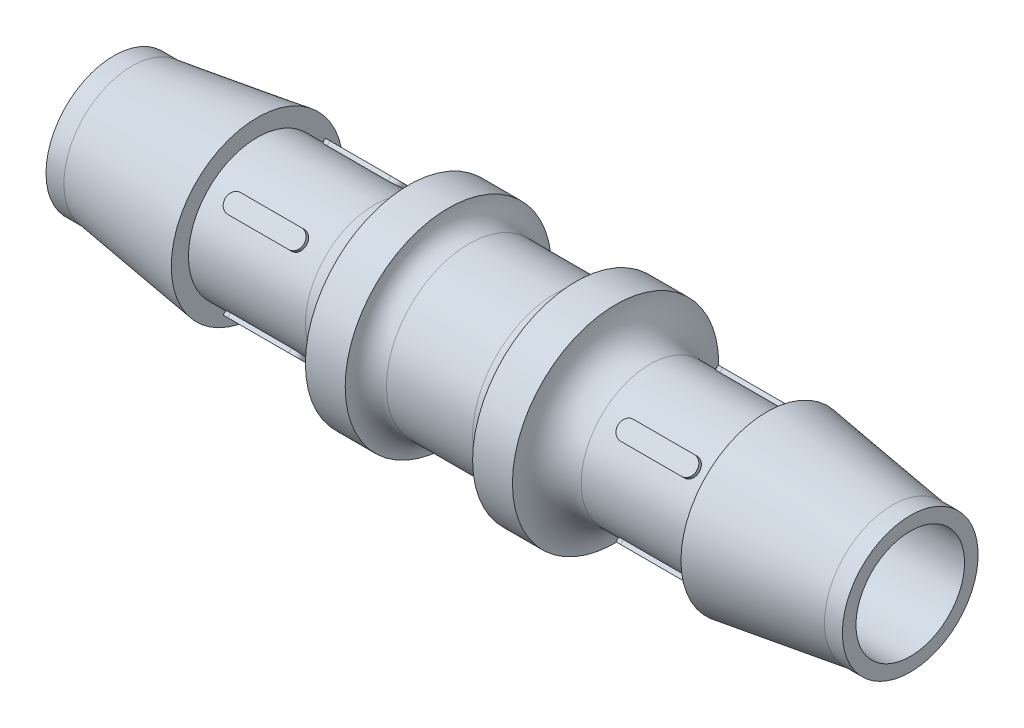
SolidWorks part; units mm, degrees
material "PVC 0.007 Plasticized"
ref_plane "Front Plane" through (0, 0, 0) normal (0, 0, 1) x (1, 0, 0)
ref_plane "Top Plane" through (0, 0, 0) normal (0, 1, 0) x (1, 0, 0)
ref_plane "Right Plane" through (0, 0, 0) normal (1, 0, 0) x (0, 0, -1)
sketch "Sketch1" plane through (0, 0, 0) normal (0, 0, 1) x (1, 0, 0)
  line L0 (0, 0) -> (33.528, 0) construction
  line L1 (33.528, 4.572) -> (33.528, 5.715)
  line L3 (21.4579, 7.239) -> (21.4579, 5.7912)
  line L4 (21.4579, 5.7912) -> (8.7173, 5.7912)
  line L5 (33.528, 5.715) -> (32.0192, 5.715)
  line L6 (8.7173, 5.7912) -> (8.7173, 8.6868)
  line L7 (8.7173, 8.6868) -> (5.3645, 8.6868)
  line L8 (5.3645, 8.6868) -> (5.3645, 6.9494)
  line L9 (5.3645, 6.9494) -> (0, 6.9494)
  line L10 (33.528, 4.572) -> (0, 4.572)
  line L11 (0, 4.572) -> (0, 6.9494)
  line L12 (15.4432, 6.5151) -> (21.4579, 6.5151) construction
  line L13 (0, 0) -> (0, -2.6412) construction
  line L14 (32.0192, 5.715) -> (21.4579, 7.239)
  dimension "D1" = 11.43
  dimension "D7" = 13.8989
  dimension "D3" = 12.0701
  dimension "D8" = 1.5088
revolve "Revolve1" add sketch "Sketch1" angle 360 about L0
sketch "Sketch2" plane through (0, 0, 0) normal (0, 0, 1) x (1, 0, 0)
  line L0 (21.4579, 5.7912) -> (8.7173, 5.7912) construction
  line L1 (8.7173, 5.7912) -> (8.7173, 8.6868) construction
  line L2 (11.6129, 5.7912) -> (8.7173, 5.7912)
  line L3 (8.7173, 5.7912) -> (8.7173, 8.6868)
  line L4 (5.3645, 8.6868) -> (5.3645, 6.9494) construction
  line L5 (5.3645, 6.9494) -> (0, 6.9494) construction
  line L6 (5.3645, 8.6868) -> (5.3645, 6.9494)
  line L7 (5.3645, 6.9494) -> (3.6271, 6.9494)
  arc A0 (8.7173, 8.6868) -> (11.6129, 5.7912) centre (11.6129, 8.6868) ccw
  arc A1 (5.3645, 8.6868) -> (3.6271, 6.9494) centre (3.6271, 8.6868) cw
revolve "Revolve2" add sketch "Sketch2" angle 360 about L0
ref_plane "Plane1" through (0, 0, 0) normal (0, 0.7071, 0.7071) x (-1, 0, 0)
sketch "Sketch3" plane through (0, 0, 0) normal (0, 0.7071, 0.7071) x (-1, 0, 0)
  line L0 (0, 0) -> (-33.528, 0) construction
  line L1 (-13.9705, 0.7544) -> (-19.1003, 0.7544)
  line L2 (-13.9705, 0.7544) -> (-13.9705, -0.7544) construction
  line L3 (-13.9705, -0.7544) -> (-19.1003, -0.7544)
  line L4 (-19.1003, 0.7544) -> (-19.1003, -0.7544) construction
  line L5 (-11.6129, 3.1148) -> (-11.6129, 5.1415) construction
  line L6 (-11.6129, 5.1415) -> (-21.4579, 5.1415) construction
  line L7 (-21.4579, 5.1415) -> (-21.4579, 3.1148) construction
  line L8 (-16.5354, 5.1415) -> (-16.5354, 0.7544) construction
  line L9 (-11.6129, 3.1148) -> (-13.2161, 3.1148) construction
  line L10 (-13.2161, 3.1148) -> (-13.2161, -0.5731) construction
  line L11 (-21.4579, 3.1148) -> (-19.8547, 3.1148) construction
  line L12 (-19.8547, 3.1148) -> (-19.8547, -0.5731) construction
  arc A0 (-19.1003, 0.7544) -> (-19.1003, -0.7544) centre (-19.1003, 0) ccw
  arc A1 (-13.9705, 0.7544) -> (-13.9705, -0.7544) centre (-13.9705, 0) cw
  dimension "D1" = 1.5088
  dimension "D2" = 6.6385
extrude "Extrude1" add sketch "Sketch3" along normal mid plane 12.1615
pattern_circular "CirPattern1" count 2 every 90 about axis through (0, 0, 0) along (1, 0, 0) of "Extrude1"
sketch "Sketch4" plane through (33.528, 0, 0) normal (1, 0, 0) x (0, 0, -1)
  circle A0 centre (0, 0) radius 4.572 construction
  circle A1 centre (0, 0) radius 4.572
extrude "Cut-Extrude1" cut sketch "Sketch4" against normal through all
mirror "Mirror1" about plane through (0, 0, 0) normal (1, 0, 0) of bodies 110
equation "\"D1@Sketch1\" = \"A@Sketch1\"*1.25"
equation "\"D3@Sketch1\" = \"C@Sketch1\"*.18"
equation "\"D4@Sketch1\" = \"C@Sketch1\"*.05"
equation "\"D6@Sketch1\" = \"C@Sketch1\"*.160/2"
equation "\"D2@Sketch1\" = \"B@Sketch1\"*.8"
equation "\"D5@Sketch1\" = \"B@Sketch1\"*1.2"
equation "\"D7@Sketch1\" = \"D2@Sketch1\"*1.2"
equation "\"D8@Sketch1\" = \"D3@Sketch1\"/8"
equation "\"D1@Sketch3\" = \"D8@Sketch1\""
equation "\"D2@Sketch3\" = \"D3@Sketch1\"*.55"
equation "\"D1@Extrude1\" = \"D2@Sketch1\"*1.05"
